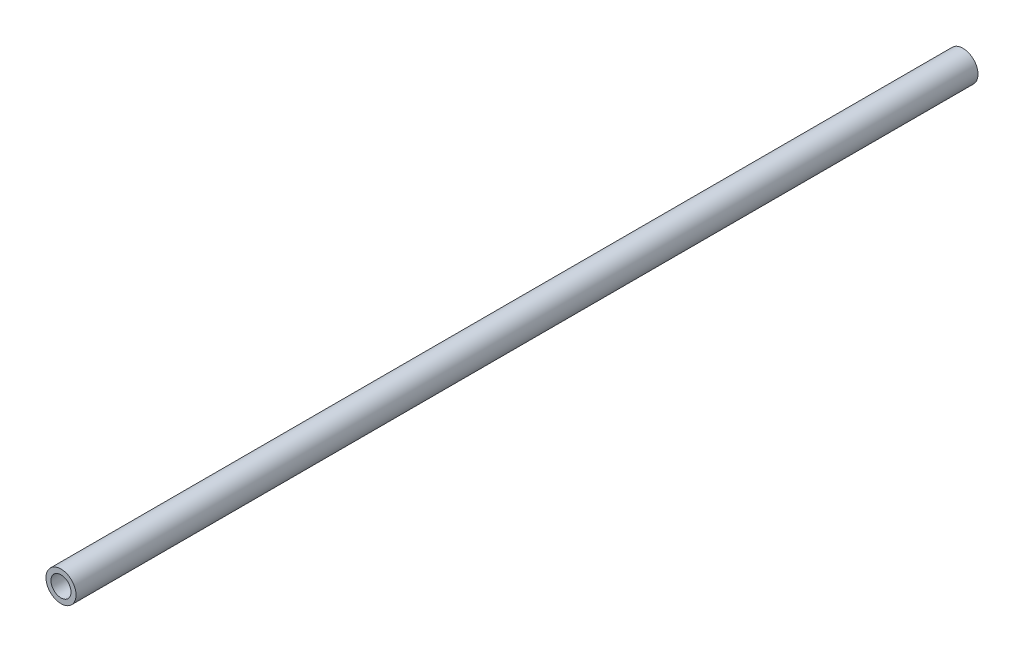
SolidWorks part; units mm, degrees
ref_plane "Front Plane" through (0, 0, 0) normal (0, 0, 1) x (1, 0, 0)
ref_plane "Top Plane" through (0, 0, 0) normal (0, 1, 0) x (1, 0, 0)
ref_plane "Right Plane" through (0, 0, 0) normal (1, 0, 0) x (0, 0, -1)
sketch "Sketch1" plane through (0, 0, 0) normal (0, 0, 1) x (1, 0, 0)
  circle A0 centre (390.7614, 31.0815) radius 7.5
  circle A1 centre (390.7614, 31.0815) radius 5
extrude "Boss-Extrude1" add sketch "Sketch1" along normal blind 450
